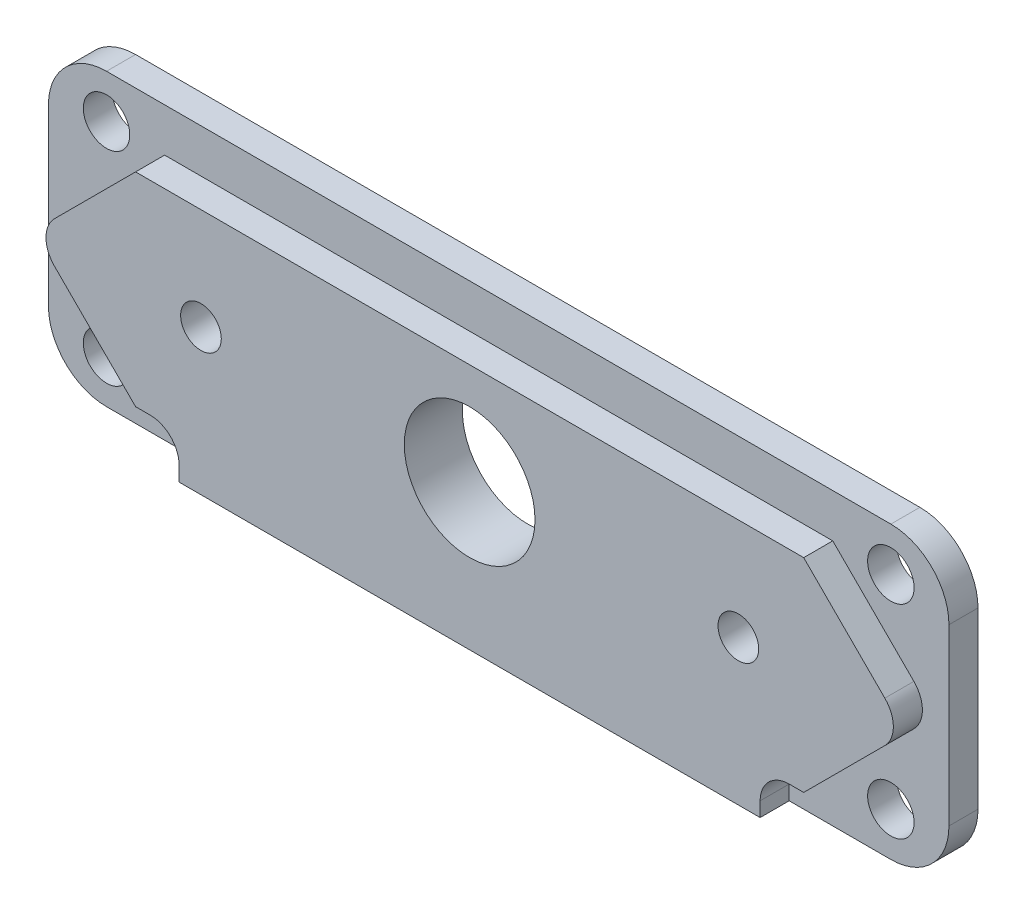
SolidWorks part; units mm, degrees
ref_plane "Front Plane" through (0, 0, 0) normal (0, 0, 1) x (1, 0, 0)
ref_plane "Top Plane" through (0, 0, 0) normal (0, 1, 0) x (1, 0, 0)
ref_plane "Right Plane" through (0, 0, 0) normal (1, 0, 0) x (0, 0, -1)
sketch "Sketch2" plane through (0, 0, 0) normal (0, 0, 1) x (1, 0, 0)
  line L1 (-27, -10) -> (27, -10)
  line L2 (-31, -6) -> (-31, 6)
  line L3 (-27, 10) -> (27, 10)
  line L4 (31, -6) -> (31, 6)
  line L5 (-31, -10) -> (31, 10) construction
  line L6 (-31, 10) -> (31, -10) construction
  arc A0 (27, 10) -> (31, 6) centre (27, 6) cw
  arc A1 (27, -10) -> (31, -6) centre (27, -6) ccw
  arc A2 (-31, 6) -> (-27, 10) centre (-27, 6) cw
  arc A3 (-31, -6) -> (-27, -10) centre (-27, -6) ccw
  point P0 (0, 0)
  dimension "D3" = 4
  dimension "D4" = 4
  dimension "D1" = 62
  dimension "D2" = 20
extrude "Boss-Extrude1" add sketch "Sketch2" along normal blind 2
sketch "Sketch3" plane through (0, 0, 2) normal (0, 0, 1) x (1, 0, 0)
  line L0 (0, 10) -> (0, -10) construction
  line L1 (27, 10) -> (-27, 10) construction
  line L2 (-27, -10) -> (27, -10) construction
  line L3 (31, 0) -> (0, 0) construction
  line L4 (31, -6) -> (31, 6) construction
  line L5 (-30, 0) -> (30, 0) construction
  line L6 (-28.5858, 1.4142) -> (-23, 7)
  line L7 (-23, 7) -> (23, 7)
  line L8 (0, 10) -> (0, -10) construction
  line L9 (28.5858, 1.4142) -> (23, 7)
  line L10 (28.5858, -1.4142) -> (23, -7)
  line L11 (-28.5858, -1.4142) -> (-23, -7)
  line L12 (-23, -7) -> (-22, -7)
  line L13 (22, -7) -> (23, -7)
  line L14 (-20, -10) -> (20, -10)
  line L15 (-20, -10) -> (-20, -9)
  line L16 (20, -10) -> (20, -9)
  arc A0 (-20, -9) -> (-22, -7) centre (-22, -9) ccw
  arc A1 (20, -9) -> (22, -7) centre (22, -9) cw
  arc A2 (28.5858, -1.4142) -> (28.5858, 1.4142) centre (27.1716, 0) ccw
  arc A3 (-28.5858, -1.4142) -> (-28.5858, 1.4142) centre (-27.1716, 0) cw
  point P17 (0, 7)
  dimension "D3" = 2
  dimension "D1" = 45
  dimension "D2" = 3
extrude "Boss-Extrude2" add sketch "Sketch3" along normal blind 2
sketch "Sketch4" plane through (0, 0, 0) normal (0, 0, -1) x (-1, 0, 0)
  line L0 (0, 10) -> (0, -10) construction
  line L1 (-27, 10) -> (27, 10) construction
  line L2 (27, -10) -> (-27, -10) construction
  line L3 (-31, 0) -> (31, 0) construction
  line L4 (-31, -6) -> (-31, 6) construction
  line L5 (31, 6) -> (31, -6) construction
  line L6 (0, 10) -> (0, -10) construction
  circle A0 centre (0, 0) radius 4.5
  circle A1 centre (-18.5, 0) radius 1.4
  circle A2 centre (18.5, 0) radius 1.4
  dimension "D1" = 18.5
extrude "Cut-Extrude1" cut sketch "Sketch4" against normal up to next
sketch "Sketch5" plane through (0, 0, 0) normal (0, 0, -1) x (-1, 0, 0)
  line L1 (-27, -7) -> (27, -7) construction
  line L2 (-27, -7) -> (-27, 7) construction
  line L3 (-27, 7) -> (27, 7) construction
  line L4 (27, -7) -> (27, 7) construction
  line L5 (-27, -7) -> (27, 7) construction
  line L6 (-27, 7) -> (27, -7) construction
  circle A0 centre (-27, 7) radius 1.6
  circle A1 centre (27, 7) radius 1.6
  circle A2 centre (27, -7) radius 1.6
  circle A3 centre (-27, -7) radius 1.6
  point P0 (0, 0)
  dimension "D1" = 54
  dimension "D2" = 14
extrude "Cut-Extrude2" cut sketch "Sketch5" against normal up to next
